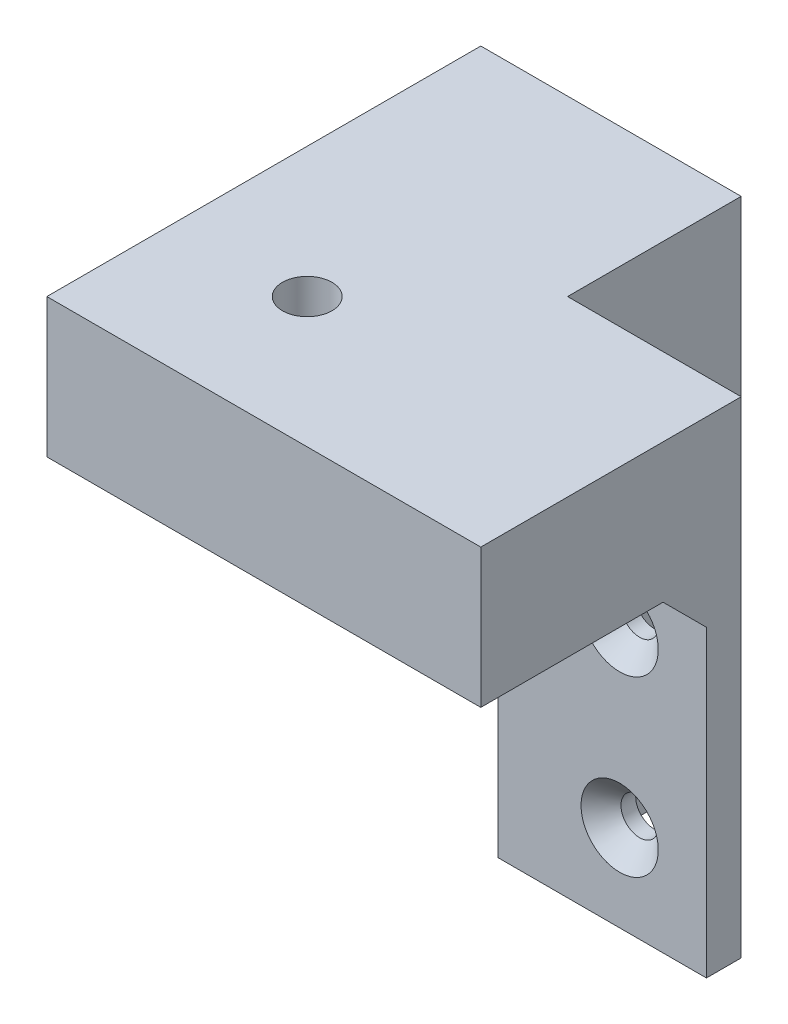
SolidWorks part; units mm, degrees
ref_plane "Front Plane" through (0, 0, 0) normal (0, 0, 1) x (1, 0, 0)
ref_plane "Top Plane" through (0, 0, 0) normal (0, 1, 0) x (1, 0, 0)
ref_plane "Right Plane" through (0, 0, 0) normal (1, 0, 0) x (0, 0, -1)
sketch "Sketch1" plane through (0, 0, 0) normal (0, 0, 1) x (1, 0, 0)
  line L0 (10, 0) -> (40, -5.3571)
  line L1 (570, -100) -> (10, 0) construction
  line L2 (10, 0) -> (-40, 0)
  line L3 (-40, 0) -> (-40, -16)
  line L4 (-40, -16) -> (38.0995, -16)
  line L5 (38.0995, -16) -> (40, -5.3571)
  dimension "D1" = 30
  dimension "D2" = 50
  dimension "D3" = 16
extrude "Boss-Extrude1" add sketch "Sketch1" along normal blind 30
sketch "Sketch2" plane through (-40, 0, 0) normal (-1, 0, 0) x (0, 0, 1)
  line L0 (0, 0) -> (-20, 0)
  line L1 (-20, 0) -> (-50, -5.3571)
  line L2 (-50, -5.3571) -> (-48.0995, -16)
  line L3 (-48.0995, -16) -> (0, -16)
  line L4 (-20, 0) -> (-580, -100) construction
  line L5 (30, -16) -> (0, -16) construction
  line L6 (0, 0) -> (0, -16)
  dimension "D1" = 30
extrude "Boss-Extrude2" add sketch "Sketch2" against normal up to surface (30 mm away)
sketch "Sketch3" plane through (0, 0, 0) normal (0, 1, 0) x (1, 0, 0)
  line L0 (-10, 0) -> (-40, -30) construction
  circle A0 centre (-25, -15) radius 2.85
  dimension "D1" = 5.7
extrude "Cut-Extrude1" cut sketch "Sketch3" against normal through all
sketch "Sketch4" plane through (0.309, 1.7305, 0) normal (0.1758, 0.9844, 0) x (0.9844, -0.1758, 0)
  line L0 (9.8443, 0) -> (40.3188, -30) construction
  circle A0 centre (25.0816, -15) radius 2.85
  dimension "D1" = 5.7
extrude "Cut-Extrude2" cut sketch "Sketch4" against normal through all
sketch "Sketch5" plane through (0, 3.4611, -0.618) normal (0, 0.9844, -0.1758) x (1, 0, 0)
  line L0 (-40, 50.1631) -> (-10, 19.6886) construction
  circle A0 centre (-25, 34.9258) radius 2.85
  dimension "D1" = 5.7
extrude "Cut-Extrude3" cut sketch "Sketch5" against normal through all
sketch "Sketch6" plane through (0, -16, 0) normal (0, -1, 0) x (1, 0, 0)
  line L0 (-10, 0) -> (-10, -20)
  line L1 (-10, -48.0995) -> (-10, 0) construction
  line L2 (-10, -20) -> (-14, -20)
  line L3 (-14, -20) -> (-14, 4)
  line L4 (-14, 4) -> (10, 4)
  line L5 (10, 4) -> (10, 0)
  line L6 (-10, 0) -> (38.0995, 0) construction
  line L7 (10, 0) -> (-10, 0)
  dimension "D1" = 20
  dimension "D2" = 4
extrude "Boss-Extrude3" add sketch "Sketch6" along normal blind 40
sketch "Sketch7" plane through (0, 0, 0) normal (0, 0, -1) x (-1, 0, 0)
  line L0 (0, -56) -> (0, 0) construction
  line L1 (10, -56) -> (-10, -56) construction
  circle A0 centre (0, -46) radius 2.15
  circle A1 centre (0, -26) radius 2.15
  dimension "D1" = 4.3
  dimension "D2" = 10
  dimension "D3" = 20
extrude "Cut-Extrude4" cut sketch "Sketch7" against normal through all
sketch "Sketch8" plane through (-10, 0, 0) normal (1, 0, 0) x (0, 0, -1)
  line L0 (10, -56) -> (10, 0) construction
  line L1 (20, -56) -> (0, -56) construction
  line L2 (0, 0) -> (20, 0) construction
  circle A0 centre (10, -46) radius 2.15
  circle A1 centre (10, -26) radius 2.15
  dimension "D1" = 4.3
  dimension "D2" = 10
  dimension "D3" = 20
extrude "Cut-Extrude5" cut sketch "Sketch8" against normal through all
chamfer "Chamfer1" distance 2.3 angle 45 4 edges at (-14, -26, -12.15) (-14, -46, -12.15) (-2.15, -46, 4) (-2.15, -26, 4)
chamfer "Chamfer2" distance 5 angle 45 2 edges at (-2, -16, 4) (-14, -16, -8)
sketch "Sketch9" plane through (0, -16, 0) normal (0, -1, 0) x (1, 0, 0)
  line L1 (10, 0) -> (40, 0)
  line L2 (10, 0) -> (10, 30)
  line L3 (10, 30) -> (40, 30)
  line L4 (40, 0) -> (40, 30)
  line L5 (-10, -20) -> (-40, -20)
  line L6 (-10, -20) -> (-10, -50)
  line L7 (-10, -50) -> (-40, -50)
  line L8 (-40, -20) -> (-40, -50)
extrude "Cut-Extrude6" cut sketch "Sketch9" against normal through all
